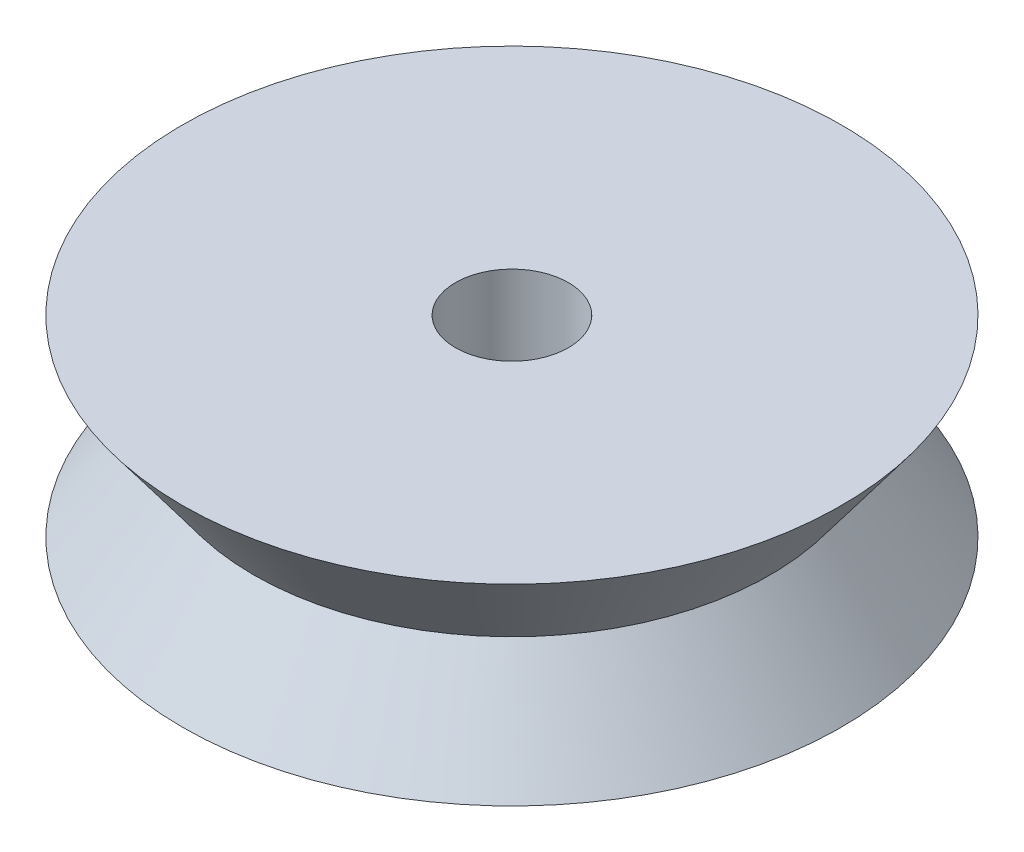
SolidWorks part; units mm, degrees
ref_plane "Alzado" through (0, 0, 0) normal (0, 0, 1) x (1, 0, 0)
ref_plane "Planta" through (0, 0, 0) normal (0, 1, 0) x (1, 0, 0)
ref_plane "Vista lateral" through (0, 0, 0) normal (1, 0, 0) x (0, 0, -1)
sketch "Croquis1" plane through (0, 0, 0) normal (0, 0, 1) x (1, 0, 0)
  line L0 (-5, 8.5) -> (-5, -8.5)
  line L1 (-5, 0) -> (-22.85, 0)
  line L2 (-22.85, 0) -> (-29.175, 8.5)
  line L3 (-29.175, 8.5) -> (-5, 8.5)
  line L4 (13.2396, 0) -> (-25.4011, 0) construction
  line L5 (0, 10.4841) -> (0, -7.2498) construction
  line L6 (-22.85, 0) -> (-29.175, -8.5)
  line L7 (-29.175, -8.5) -> (-5, -8.5)
  dimension "D1" = 5
  dimension "D2" = 8.5
  dimension "D3" = 22.85
  dimension "D4" = 29.175
revolve "Revolución1" add sketch "Croquis1" angle 360 about L5
